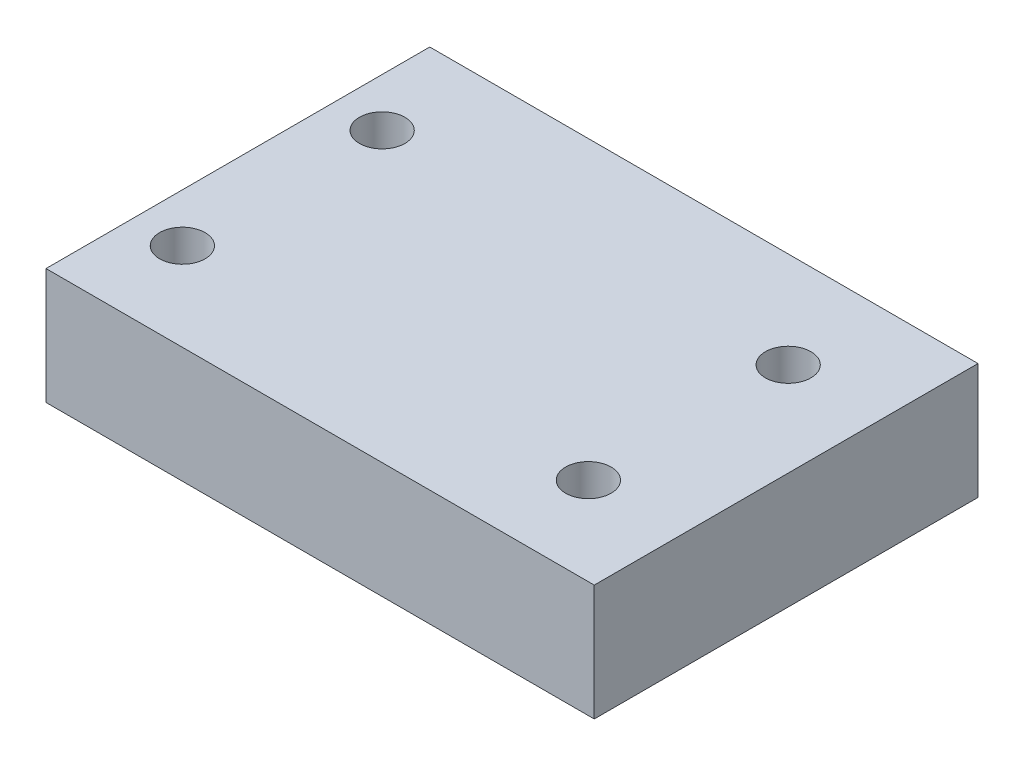
SolidWorks part; units mm, degrees
ref_plane "Front Plane" through (0, 0, 0) normal (0, 0, 1) x (1, 0, 0)
ref_plane "Top Plane" through (0, 0, 0) normal (0, 1, 0) x (1, 0, 0)
ref_plane "Right Plane" through (0, 0, 0) normal (1, 0, 0) x (0, 0, -1)
sketch "Sketch1" plane through (0, 0, 0) normal (0, 1, 0) x (1, 0, 0)
  line L0 (-30.0101, 0) -> (30.0101, 0) construction
  line L1 (0, -21.0058) -> (0, 21.0058) construction
  line L7 (-30.0101, 21.0058) -> (30.0101, 21.0058)
  line L8 (-30.0101, 21.0058) -> (-30.0101, -21.0058)
  line L9 (-30.0101, -21.0058) -> (30.0101, -21.0058)
  line L10 (30.0101, 21.0058) -> (30.0101, -21.0058)
  line L11 (-30.0101, 21.0058) -> (30.0101, -21.0058) construction
  line L12 (-30.0101, -21.0058) -> (30.0101, 21.0058) construction
  point P0 (0, 0)
extrude "Boss-Extrude1" add sketch "Sketch1" along normal blind 12.7
sketch "Sketch2" plane through (0, 12.7, 0) normal (0, 1, 0) x (1, 0, 0)
  line L0 (-30.0101, 21.0058) -> (-24.7101, 21.0058) construction
  line L1 (30.0101, 21.0058) -> (-30.0101, 21.0058) construction
  line L2 (-24.7101, 21.0058) -> (-24.7101, 10.4948) construction
  line L4 (-24.7101, 10.4948) -> (19.7399, 10.4948) construction
  line L5 (-24.7101, 10.4948) -> (-24.7101, -11.3792) construction
  line L6 (-24.7101, -11.3792) -> (19.7399, -11.3792) construction
  line L7 (19.7399, 10.4948) -> (19.7399, -11.3792) construction
  dimension "D1" = 5.3
  dimension "D2" = 10.511
hole_wizard "#10 Clearance Hole1" positions "Sketch3" profile "Sketch4" hole size "#10" standard "ANSI Inch" end condition through all
sketch "Sketch3" plane through (0, 12.7, 0) normal (0, 1, 0) x (1, 0, 0)
  point P0 (-24.7101, 10.4948)
  point P3 (-24.7101, -11.3792)
  point P6 (19.7399, -11.3792)
  point P9 (19.7399, 10.4948)
sketch "Sketch4" plane through (-24.7101, 12.7, -10.4948) normal (1, 0, 0) x (0, 0, 1)
  line L0 (0, 0) -> (0, 12.7)
  line L1 (0, 12.7) -> (2.4892, 12.7)
  line L2 (2.4892, 12.7) -> (2.4892, 0)
  line L5 (2.4892, 0) -> (0, 0)
  line L11 (0, -6.35) -> (0, 107.95) construction
  dimension "Thru Hole Dia." = 4.9784
  dimension "Thru Hole Depth" = 12.7
